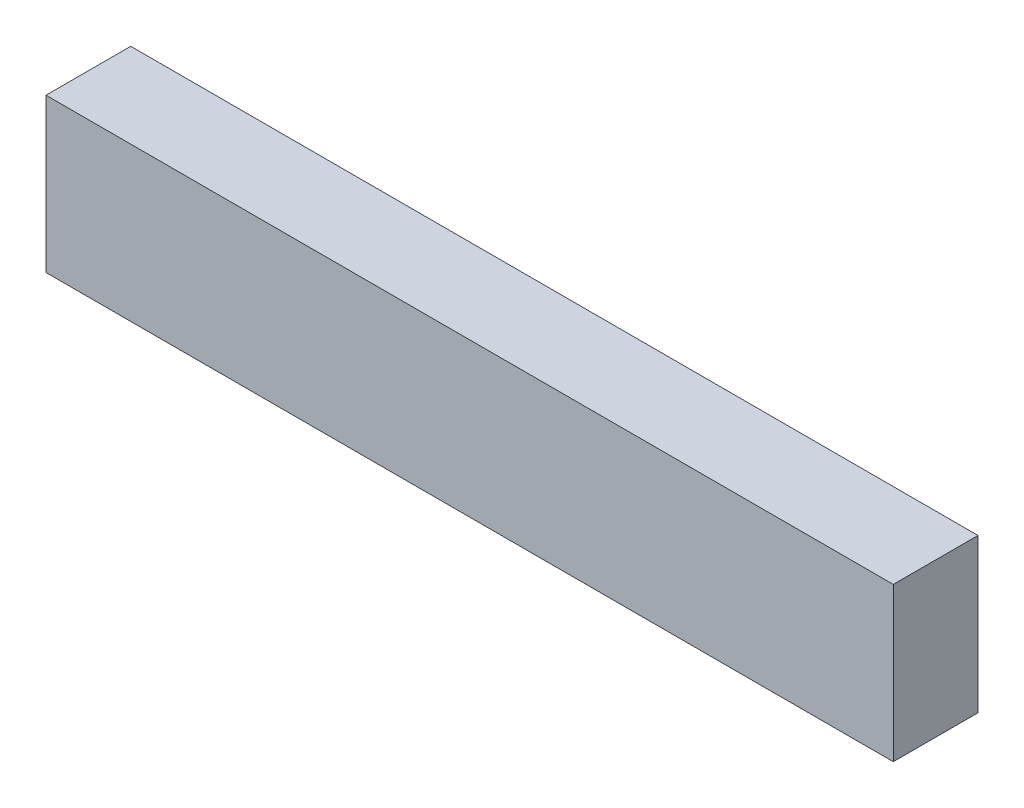
SolidWorks part; units mm, degrees
material "Maple"
ref_plane "Front Plane" through (0, 0, 0) normal (0, 0, 1) x (1, 0, 0)
ref_plane "Top Plane" through (0, 0, 0) normal (0, 1, 0) x (1, 0, 0)
ref_plane "Right Plane" through (0, 0, 0) normal (1, 0, 0) x (0, 0, -1)
sketch "Sketch1" plane through (0, 0, 0) normal (0, 1, 0) x (1, 0, 0)
  line L1 (40, 4) -> (-40, 4)
  line L2 (40, 4) -> (40, -4)
  line L3 (40, -4) -> (-40, -4)
  line L4 (-40, 4) -> (-40, -4)
  line L5 (40, 4) -> (-40, -4) construction
  line L6 (40, -4) -> (-40, 4) construction
  point P0 (0, 0)
  dimension "D1" = 80
  dimension "D2" = 8
extrude "Boss-Extrude1" add sketch "Sketch1" along normal blind 14.5
